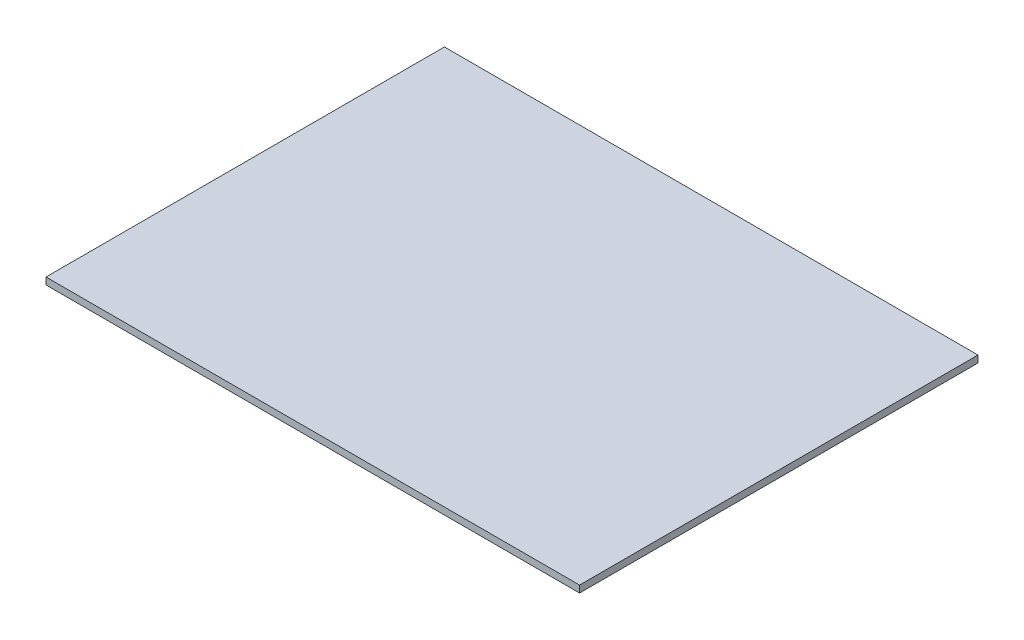
SolidWorks part; units mm, degrees
ref_plane "Спереди" through (0, 0, 0) normal (0, 0, 1) x (1, 0, 0)
ref_plane "Сверху" through (0, 0, 0) normal (0, 1, 0) x (1, 0, 0)
ref_plane "Справа" through (0, 0, 0) normal (1, 0, 0) x (0, 0, -1)
sketch "Эскиз1" plane through (0, 0, 0) normal (0, 1, 0) x (1, 0, 0)
  line L1 (-229.2456, 83.6278) -> (78.7544, 83.6278)
  line L2 (-229.2456, 83.6278) -> (-229.2456, -146.3722)
  line L3 (-229.2456, -146.3722) -> (78.7544, -146.3722)
  line L4 (78.7544, 83.6278) -> (78.7544, -146.3722)
  dimension "D1" = 308
  dimension "D2" = 230
extrude "Бобышка-Вытянуть1" add sketch "Эскиз1" along normal blind 4
